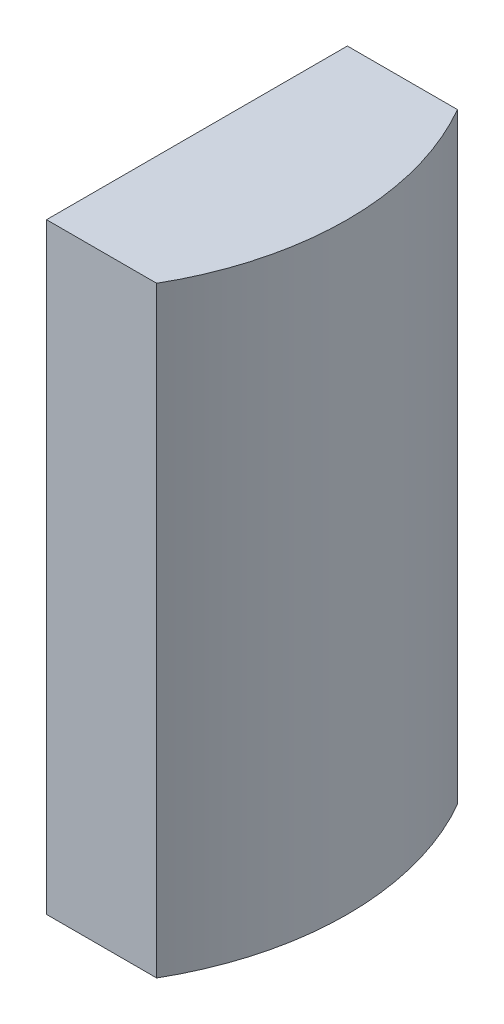
SolidWorks part; units mm, degrees
ref_plane "Спереди" through (0, 0, 0) normal (0, 0, 1) x (1, 0, 0)
ref_plane "Сверху" through (0, 0, 0) normal (0, 1, 0) x (1, 0, 0)
ref_plane "Справа" through (0, 0, 0) normal (1, 0, 0) x (0, 0, -1)
sketch "Эскиз1" plane through (0, 0, 0) normal (0, 1, 0) x (1, 0, 0)
  line L2 (1.0012, 2) -> (1.7333, 2)
  line L3 (1.0012, 2) -> (1.0012, 0)
  line L4 (1.0012, 0) -> (1.7333, 0)
  arc A0 (1.7333, 0) -> (1.7333, 2) centre (0, 1) ccw
extrude "Бобышка-Вытянуть1" add sketch "Эскиз1" along normal blind 4
